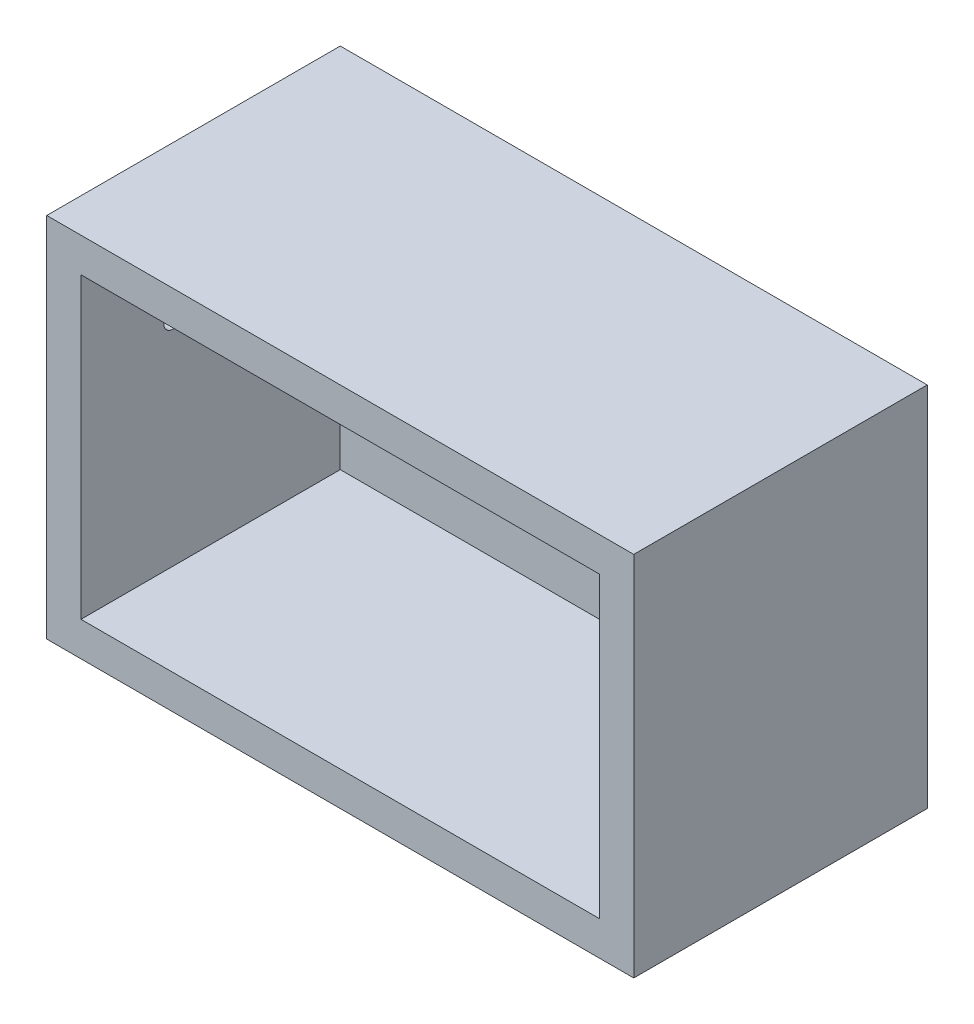
SolidWorks part; units mm, degrees
ref_plane "Přední rovina" through (0, 0, 0) normal (0, 0, 1) x (1, 0, 0)
ref_plane "Horní rovina" through (0, 0, 0) normal (0, 1, 0) x (1, 0, 0)
ref_plane "Pravá rovina" through (0, 0, 0) normal (1, 0, 0) x (0, 0, -1)
sketch "Skica1" plane through (0, 0, 0) normal (0, 0, 1) x (1, 0, 0)
  line L1 (-60, 37.5) -> (60, 37.5)
  line L2 (-60, 37.5) -> (-60, -37.5)
  line L3 (-60, -37.5) -> (60, -37.5)
  line L4 (60, 37.5) -> (60, -37.5)
  line L5 (-60, 37.5) -> (60, -37.5) construction
  line L6 (-60, -37.5) -> (60, 37.5) construction
  point P0 (0, 0)
  dimension "D1" = 120
  dimension "D2" = 75
extrude "Přidat vysunutím9" add sketch "Skica1" along normal blind 7 contours L1 L4 L3 L2
sketch "Skica9" plane through (-60, 0, 0) normal (-1, 0, 0) x (0, 0, 1)
  line L1 (0, -37.5) -> (60, -37.5)
  line L2 (0, -37.5) -> (0, 37.5)
  line L3 (0, 37.5) -> (60, 37.5)
  line L4 (60, -37.5) -> (60, 37.5)
  dimension "D1" = 60
  dimension "D2" = 75
extrude "Přidat vysunutím10" add sketch "Skica9" against normal blind 7
sketch "Skica10" plane through (60, 0, 0) normal (1, 0, 0) x (0, 0, -1)
  line L1 (0, -37.5) -> (-60, -37.5)
  line L2 (0, -37.5) -> (0, 37.5)
  line L3 (0, 37.5) -> (-60, 37.5)
  line L4 (-60, -37.5) -> (-60, 37.5)
extrude "Přidat vysunutím11" add sketch "Skica10" against normal blind 7
sketch "Skica11" plane through (0, -37.5, 0) normal (0, -1, 0) x (-1, 0, 0)
  line L1 (60, 0) -> (-60, 0)
  line L2 (60, 0) -> (60, -60)
  line L3 (60, -60) -> (-60, -60)
  line L4 (-60, 0) -> (-60, -60)
extrude "Přidat vysunutím12" add sketch "Skica11" against normal blind 7
sketch "Skica12" plane through (0, 37.5, 0) normal (0, 1, 0) x (1, 0, 0)
  line L1 (-60, 0) -> (60, 0)
  line L2 (-60, 0) -> (-60, -60)
  line L3 (-60, -60) -> (60, -60)
  line L4 (60, 0) -> (60, -60)
extrude "Přidat vysunutím13" add sketch "Skica12" against normal blind 7
sketch "Skica13" plane through (-60, 0, 0) normal (-1, 0, 0) x (0, 0, 1)
  line L0 (60, 37.5) -> (0, 37.5) construction
  line L1 (9, 17.5) -> (16.3, 17.5)
  line L2 (9, 17.5) -> (9, 9)
  line L3 (9, 9) -> (16.3, 9)
  line L4 (16.3, 17.5) -> (16.3, 9)
  line L5 (9, 17.5) -> (16.3, 9) construction
  line L6 (9, 9) -> (16.3, 17.5) construction
  line L7 (0, 37.5) -> (0, -37.5) construction
  circle A0 centre (41.3, 13.25) radius 1.75
  point P0 (12.65, 13.25)
  point P7 (9, 13.25)
  dimension "D5" = 3.5
  dimension "D6" = 25
  dimension "D1" = 20
  dimension "D2" = 9
  dimension "D3" = 8.5
  dimension "D4" = 7.3
extrude "Odebrat vysunutím1" cut sketch "Skica13" against normal blind 7
